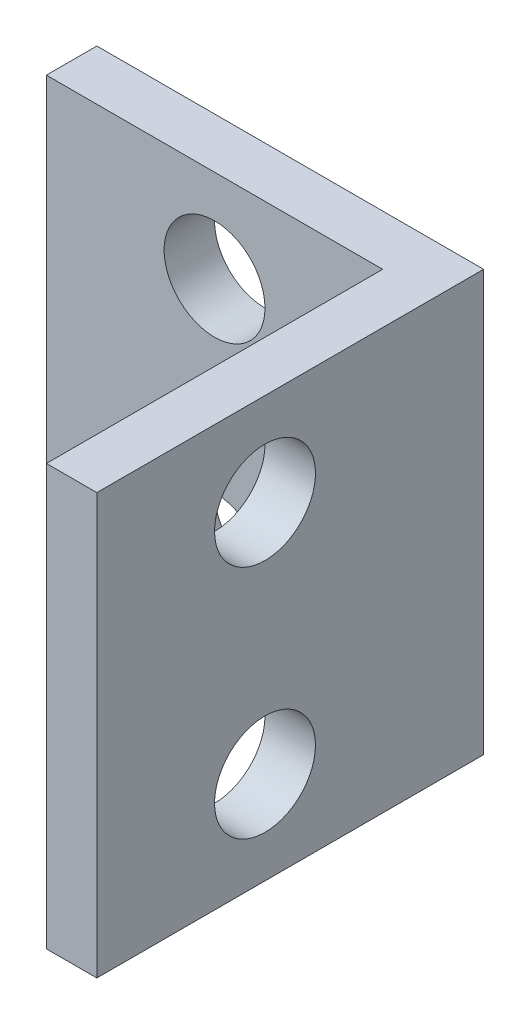
SolidWorks part; units mm, degrees
ref_plane "Front Plane" through (0, 0, 0) normal (0, 0, 1) x (1, 0, 0)
ref_plane "Top Plane" through (0, 0, 0) normal (0, 1, 0) x (1, 0, 0)
ref_plane "Right Plane" through (0, 0, 0) normal (1, 0, 0) x (0, 0, -1)
sketch "Sketch1" plane through (0, 0, 0) normal (0, 0, 1) x (1, 0, 0)
  line L1 (-10, -12.5) -> (10, -12.5)
  line L2 (-10, -12.5) -> (-10, 12.5)
  line L3 (-10, 12.5) -> (10, 12.5)
  line L4 (10, -12.5) -> (10, 12.5)
  line L5 (-10, -12.5) -> (10, 12.5) construction
  line L6 (-10, 12.5) -> (10, -12.5) construction
  point P0 (0, 0)
  dimension "D1" = 20
  dimension "D2" = 25
extrude "Boss-Extrude1" add sketch "Sketch1" along normal blind 3
sketch "Sketch3" plane through (10, 0, 0) normal (1, 0, 0) x (0, 0, -1)
  line L1 (0, 12.5) -> (-23, 12.5)
  line L2 (0, 12.5) -> (0, -12.5)
  line L3 (0, -12.5) -> (-23, -12.5)
  line L4 (-23, 12.5) -> (-23, -12.5)
  dimension "D1" = 23
  dimension "D2" = 25
extrude "Boss-Extrude2" add sketch "Sketch3" along normal blind 3
sketch "Sketch4" plane through (0, 0, 3) normal (0, 0, 1) x (1, 0, 0)
  line L0 (0, 0) -> (0, 12.5) construction
  line L1 (10, 12.5) -> (-10, 12.5) construction
  line L2 (-10, 0) -> (10, 0) construction
  line L3 (-10, 12.5) -> (-10, -12.5) construction
  line L4 (10, -12.5) -> (10, 12.5) construction
  circle A0 centre (0, 7) radius 3
  circle A1 centre (0, -7) radius 3
  dimension "D1" = 6
  dimension "D2" = 7
extrude "Cut-Extrude1" cut sketch "Sketch4" against normal through all
sketch "Sketch5" plane through (10, 0, 0) normal (-1, 0, 0) x (0, 0, 1)
  line L0 (23, 0) -> (3, 0) construction
  line L1 (23, 12.5) -> (23, -12.5) construction
  line L2 (3, -12.5) -> (3, 12.5) construction
  line L3 (13, 0) -> (13, 12.5) construction
  line L4 (3, 12.5) -> (23, 12.5) construction
  circle A0 centre (13, 7) radius 3
  circle A1 centre (13, -7) radius 3
  dimension "D1" = 6
  dimension "D2" = 7
extrude "Cut-Extrude2" cut sketch "Sketch5" against normal through all
